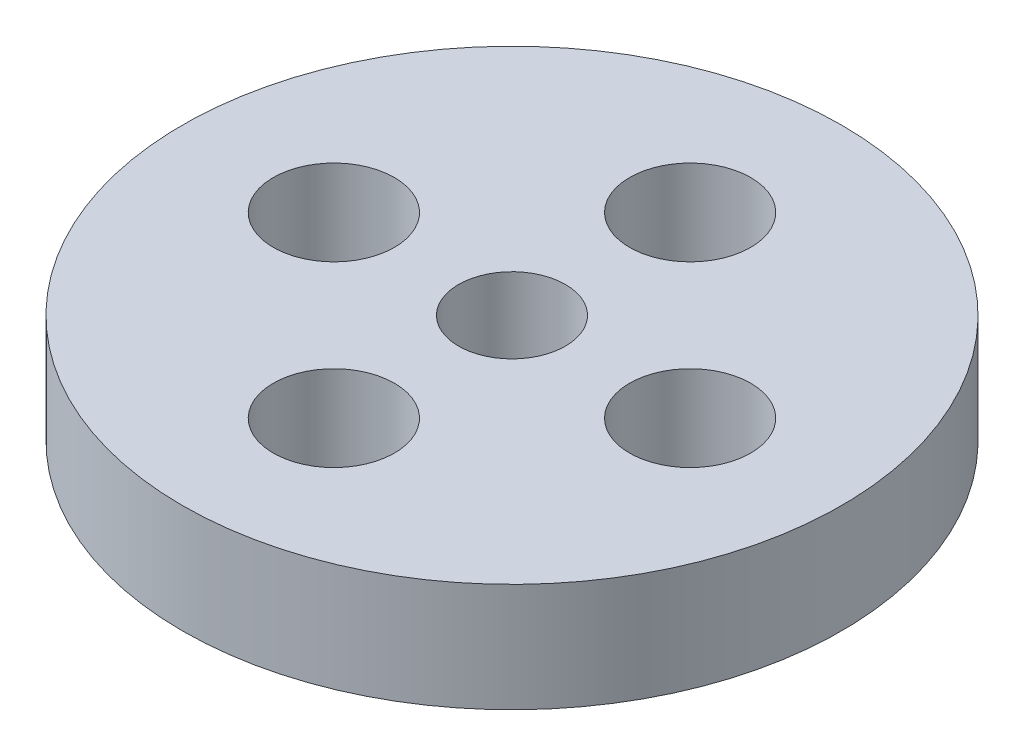
SolidWorks part; units mm, degrees
ref_plane "Front Plane" through (0, 0, 0) normal (0, 0, 1) x (1, 0, 0)
ref_plane "Top Plane" through (0, 0, 0) normal (0, 1, 0) x (1, 0, 0)
ref_plane "Right Plane" through (0, 0, 0) normal (1, 0, 0) x (0, 0, -1)
sketch "Sketch1" plane through (0, 0, 0) normal (0, 1, 0) x (1, 0, 0)
  circle A1 centre (0, 0) radius 9.25
  circle A3 centre (0, 5) radius 1.7
  circle A5 centre (-5, 0) radius 1.7
  circle A9 centre (0, -5) radius 1.7
  circle A10 centre (5, 0) radius 1.7
  circle A11 centre (0, 0) radius 1.5
extrude "Boss-Extrude1" add sketch "Sketch1" along normal blind 3.048 separate body
